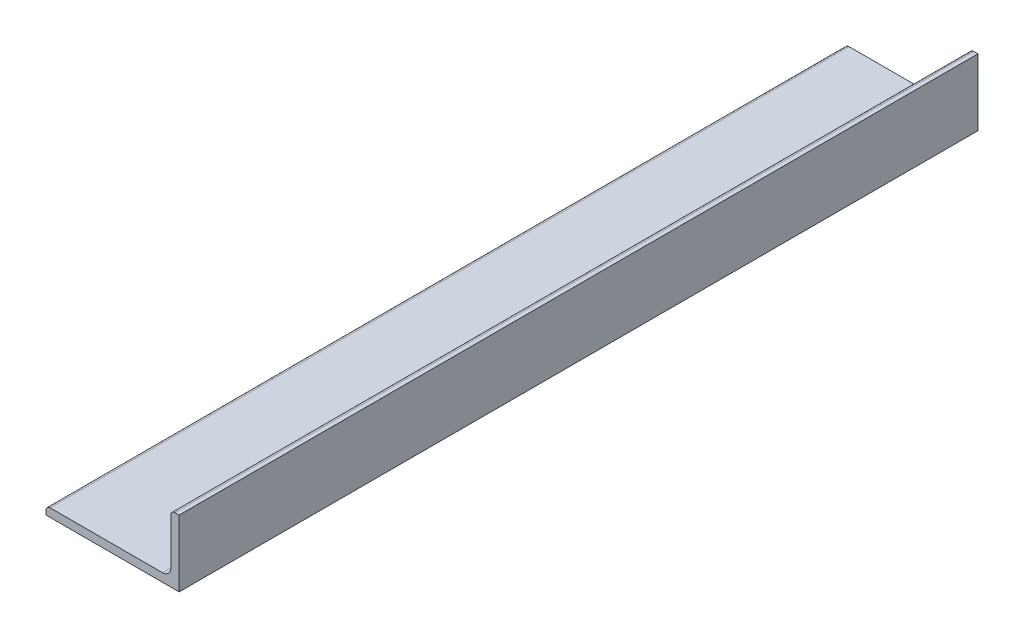
SolidWorks part; units mm, degrees
ref_plane "Front Plane" through (0, 0, 0) normal (0, 0, 1) x (1, 0, 0)
ref_plane "Top Plane" through (0, 0, 0) normal (0, 1, 0) x (1, 0, 0)
ref_plane "Right Plane" through (0, 0, 0) normal (1, 0, 0) x (0, 0, -1)
sketch "Sketch0" plane through (0, 0, 0) normal (0, 0, 1) x (1, 0, 0)
  line L0 (-25.4, -12.7) -> (25.4, -12.7)
  line L1 (25.4, -12.7) -> (25.4, 12.7)
  line L2 (25.4, 0) -> (0, 0) construction
  line L3 (0, 0) -> (0, -12.7) construction
  line L4 (22.225, -6.35) -> (22.225, 12.7) construction
  line L5 (19.05, -9.525) -> (-25.4, -9.525) construction
  arc A0 (22.225, -6.35) -> (19.05, -9.525) centre (19.05, -6.35) cw
  point P3 (21.2951, -8.5951)
  dimension "Inside Corner Radius" = 3.175
  dimension "Outside Height" = 25.4
  dimension "Inside Height" = 22.225
  dimension "Inside Width" = 47.625
  dimension "Wall Thickness" = 3.175
  dimension "D1" = 3.175
  dimension "Outside Width" = 50.8
sketch "Sketch1" plane through (0, 0, 0) normal (1, 0, 0) x (0, 0, -1)
  line L0 (152.4, 0) -> (-152.4, 0)
  point P4 (0, 0)
  dimension "Length" = 304.8
sketch "Sketch2" plane through (0, 0, 0) normal (0, 0, 1) x (1, 0, 0)
  line L0 (-25.4, -12.7) -> (25.4, -12.7)
  line L1 (25.4, -12.7) -> (25.4, 12.7)
  line L2 (25.4, 12.7) -> (22.225, 12.7) construction
  line L3 (22.225, 11.1125) -> (22.225, -6.35)
  line L4 (19.05, -9.525) -> (-23.8125, -9.525)
  line L5 (-25.4, -12.7) -> (-25.4, -9.525) construction
  line L6 (23.8125, 12.7) -> (25.4, 12.7)
  line L7 (-25.4, -11.1125) -> (-25.4, -12.7)
  line L8 (25.4, 0) -> (0, 0) construction
  line L9 (0, 0) -> (0, -12.7) construction
  arc A0 (22.225, 11.1125) -> (23.8125, 12.7) centre (23.8125, 11.1125) cw
  arc A1 (-25.4, -11.1125) -> (-23.8125, -9.525) centre (-23.8125, -11.1125) cw
  arc A2 (22.225, -6.35) -> (19.05, -9.525) centre (19.05, -6.35) cw
  dimension "Inside Radius" = 3.175
  dimension "Height" = 25.4
  dimension "Width" = 50.8
  dimension "Thickness" = 3.175
extrude "Boss-Extrude1" add sketch "Sketch2" along normal mid plane 304.8
sketch "Break Locations" plane through (0, 0, 0) normal (1, 0, 0) x (0, 0, -1)
  line L0 (-126.492, 0) -> (126.492, 0)
  line L1 (-152.4, -12.7) -> (-152.4, 12.7) construction
  line L2 (152.4, -12.7) -> (152.4, 12.7) construction
  point P0 (-130.81, 0)
  point P1 (130.81, 0)
  point P10 (0, 0)
  point P11 (126.492, 0)
  point P13 (-126.492, 0)
  dimension "D1" = 21.59
  dimension "D2" = 21.59
  dimension "D3" = 25.908
equation "\"D1@Break Locations\" = .85 * \"Height@Sketch2\""
equation "\"D2@Break Locations\"=\"D1@Break Locations\""
equation "\"Thickness@Sketch2\"=\"wall thickness@sketch0\""
equation "\"Height@Sketch2\"=\"outside height@sketch0\""
equation "\"Width@Sketch2\"=\"outside width@sketch0\""
equation "\"Inside Radius@Sketch2\"=\"inside corner radius@sketch0\""
equation "\"Length@Boss-Extrude1\"=\"length@sketch1\""
equation "\"D3@Break Locations\"=\"D2@Break Locations\"*1.2"
equation "\"D1@Sketch0\"=\"Wall Thickness@Sketch0\""
